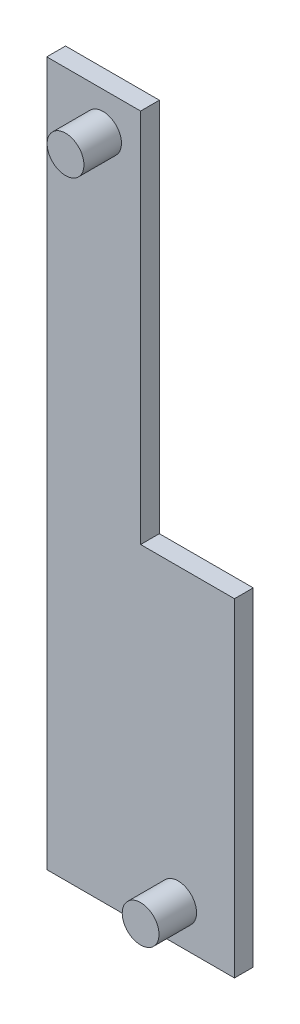
SolidWorks part; units mm, degrees
ref_plane "Front Plane" through (0, 0, 0) normal (0, 0, 1) x (1, 0, 0)
ref_plane "Top Plane" through (0, 0, 0) normal (0, 1, 0) x (1, 0, 0)
ref_plane "Right Plane" through (0, 0, 0) normal (1, 0, 0) x (0, 0, -1)
sketch "Sketch1" plane through (0, 0, 0) normal (0, 0, 1) x (1, 0, 0)
  line L1 (0, 0) -> (50, 0)
  line L2 (0, 0) -> (0, 187.5)
  line L3 (0, 187.5) -> (50, 187.5)
  line L4 (50, 0) -> (50, 187.5)
  dimension "D1" = 50
  dimension "D2" = 187.5
extrude "Boss-Extrude1" add sketch "Sketch1" along normal blind 5
sketch "Sketch2" plane through (0, 0, 5) normal (0, 0, 1) x (1, 0, 0)
  line L0 (0, 0) -> (50, 0) construction
  line L1 (0, 187.5) -> (0, 0) construction
  line L2 (50, 187.5) -> (0, 187.5) construction
  circle A0 centre (35, 10) radius 4.9
  circle A1 centre (15, 177.5) radius 4.9
  dimension "D1" = 9.8
  dimension "D2" = 10
  dimension "D3" = 35
  dimension "D4" = 10
  dimension "D5" = 9.8
  dimension "D6" = 15
extrude "Boss-Extrude2" add sketch "Sketch2" along normal blind 10
sketch "Sketch3" plane through (0, 0, 5) normal (0, 0, 1) x (1, 0, 0)
  line L1 (25, 187.5) -> (50, 187.5)
  line L2 (25, 187.5) -> (25, 87.5)
  line L3 (25, 87.5) -> (50, 87.5)
  line L4 (50, 187.5) -> (50, 87.5)
  dimension "D1" = 25
  dimension "D2" = 100
extrude "Cut-Extrude1" cut sketch "Sketch3" against normal blind 10
